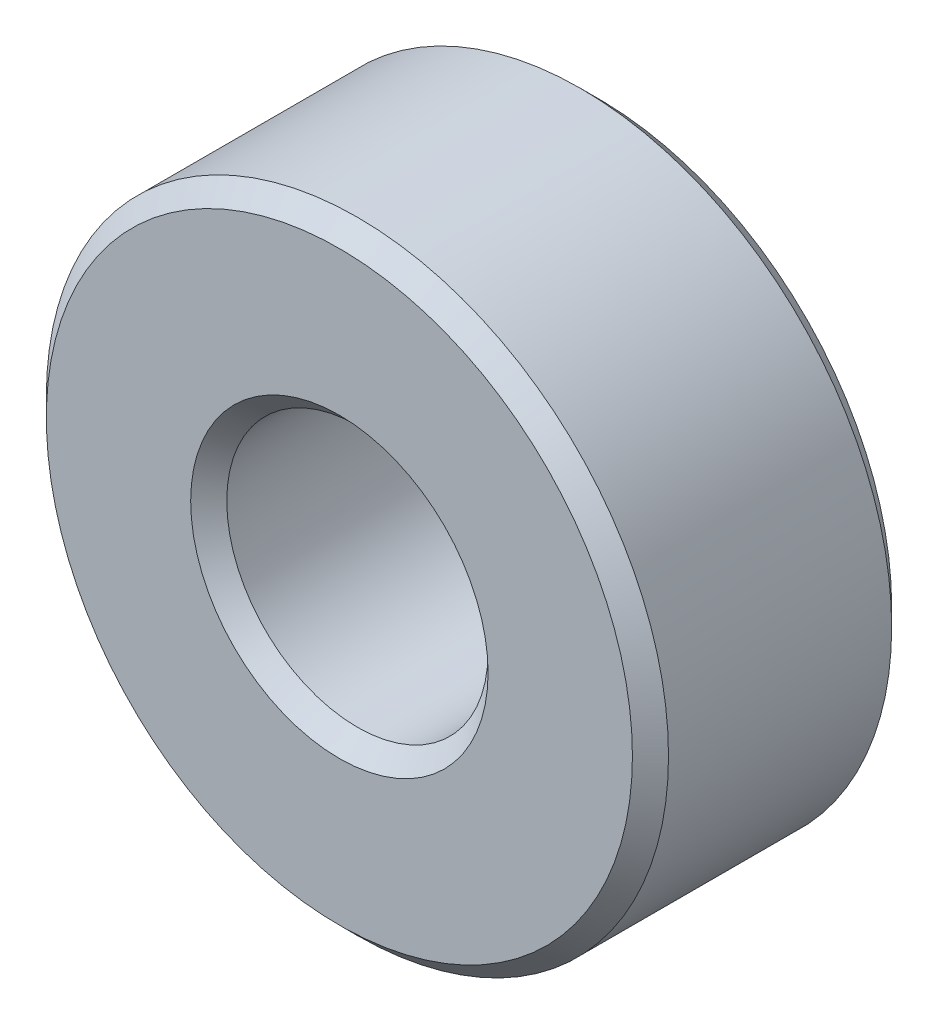
SolidWorks part; units mm, degrees
material "PE Low/Medium Density"
ref_plane "Front Plane" through (0, 0, 0) normal (0, 0, 1) x (1, 0, 0)
ref_plane "Top Plane" through (0, 0, 0) normal (0, 1, 0) x (1, 0, 0)
ref_plane "Right Plane" through (0, 0, 0) normal (1, 0, 0) x (0, 0, -1)
sketch "Sketch1" plane through (0, 0, 0) normal (0, 0, 1) x (1, 0, 0)
  circle A0 centre (0, 0) radius 9.525 construction
  circle A1 centre (0, 0) radius 4.0005 construction
  point P4 (0, 9.525)
  dimension "ID" = 8.001
  dimension "OD" = 19.05
sketch "Sketch2" plane through (0, 0, 0) normal (1, 0, 0) x (0, 0, -1)
  line L0 (-3.9688, 9.525) -> (3.9688, 9.525) construction
  dimension "Length" = 7.9375
sketch "Sketch3" plane through (0, 0, 0) normal (0, 0, 1) x (1, 0, 0)
  circle A0 centre (0, 0) radius 4.0005 construction
  circle A1 centre (0, 0) radius 9.525 construction
  circle A2 centre (0, 0) radius 4.0005
  circle A3 centre (0, 0) radius 9.525
extrude "Boss-Extrude1" add sketch "Sketch3" against normal up to vertex (3.9688 mm away) and the other way up to vertex (3.9688 mm away) up to point (0, 9.525, -3.9688) other way up to point (0, 9.525, 3.9688)
chamfer "Chamfer1" distance 0.5524 angle 45 1 edges at (9.525, 0, 3.9688)
equation "\"D1@Chamfer1\"=(\"OD@Sketch1\"-\"ID@Sketch1\")*0.05"
